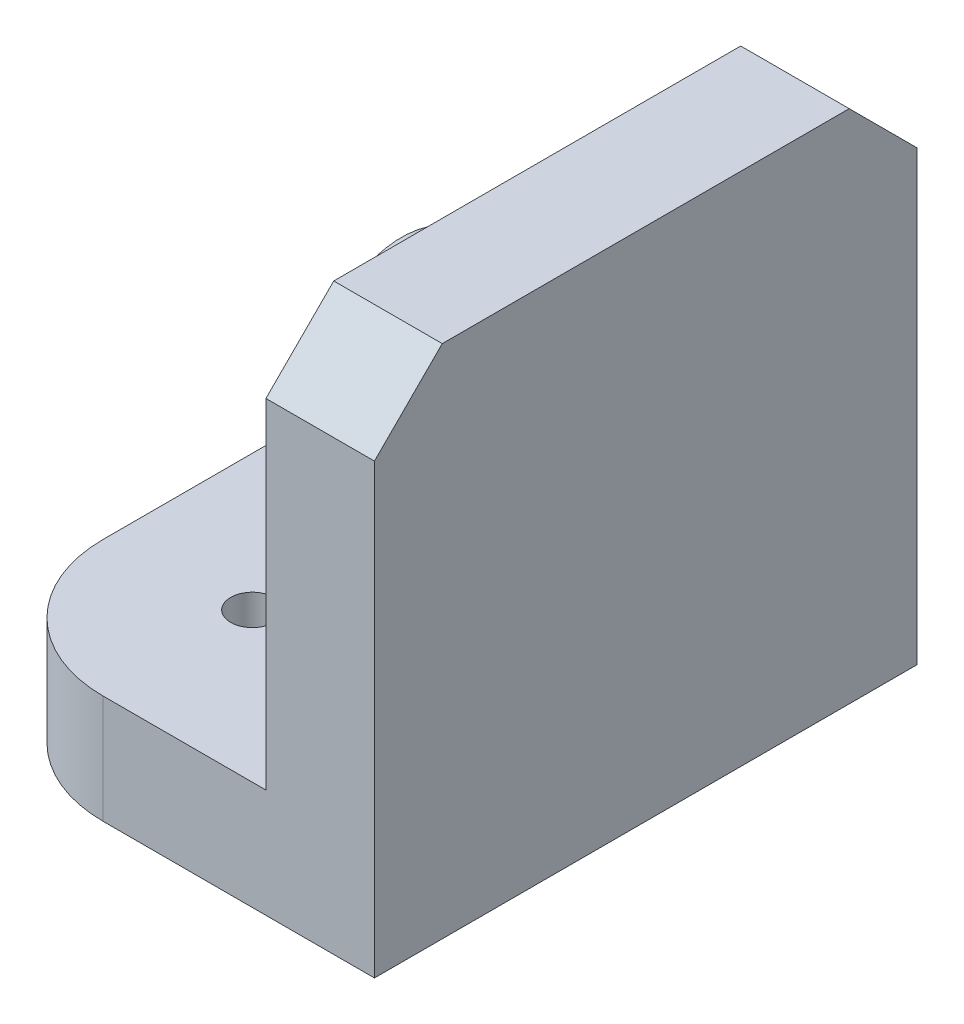
SolidWorks part; units mm, degrees
ref_plane "Alzado" through (0, 0, 0) normal (0, 0, 1) x (1, 0, 0)
ref_plane "Planta" through (0, 0, 0) normal (0, 1, 0) x (1, 0, 0)
ref_plane "Vista lateral" through (0, 0, 0) normal (1, 0, 0) x (0, 0, -1)
sketch "Croquis1" plane through (0, 0, 0) normal (0, 0, 1) x (1, 0, 0)
  line L0 (0, 39.1441) -> (0, -9.5542) construction
  line L3 (-4, 4) -> (4, 4)
  line L5 (-494, -4) -> (6, -4) construction
  line L6 (4, 4) -> (-26, 4)
  line L7 (-4, 4) -> (4, 4)
  line L8 (-4, 4) -> (-4, 34)
  line L9 (-4, 34) -> (4, 34)
  line L10 (4, 4) -> (4, 34)
  line L11 (4, 4) -> (4, -4)
  line L12 (4, -4) -> (-26, -4)
  line L13 (-26, 4) -> (-26, -4)
  point P0 (0, 0)
  dimension "D1" = 8
  dimension "D2" = 30
  dimension "D3" = 30
  dimension "D4" = 8
extrude "Saliente-Extruir1" add sketch "Croquis1" along normal mid plane 40 contours L0 L9 L8 L3 | L9 L0 L7 L10 | L0 L3 L6 L13 L12 | L7 L0 L12 L11
sketch "Croquis2" plane through (-4, 0, 0) normal (-1, 0, 0) x (0, 0, 1)
  line L0 (-20.6639, 17.8) -> (22.1929, 17.8) construction
  line L1 (20, -4) -> (-20, -4) construction
  line L2 (0, 0) -> (0, 34) construction
  line L3 (20, 34) -> (-20, 34) construction
  circle A0 centre (0, 17.85) radius 6.44
  dimension "D2" = 12.88
  dimension "D1" = 21.8
extrude "Saliente-Extruir2" add sketch "Croquis2" along normal blind 10
chamfer "Chaflán1" distance 5 angle 45 2 edges at (0, 34, -20) (0, 34, 20)
fillet "Redondeo1" radius 10 2 edges at (-26, 0, -20) (-26, 0, 20)
sketch "Croquis3" plane through (0, -4, 0) normal (0, -1, 0) x (1, 0, 0)
  line L0 (6.8023, 0) -> (-31.6574, 0) construction
  line L2 (-26, 10) -> (-26, -10) construction
  circle A0 centre (-16, 9) radius 1.6
  circle A1 centre (-16, -9) radius 1.6
  dimension "D1" = 3.2
  dimension "D2" = 9
  dimension "D3" = 10
extrude "Cortar-Extruir1" cut sketch "Croquis3" against normal blind 10
